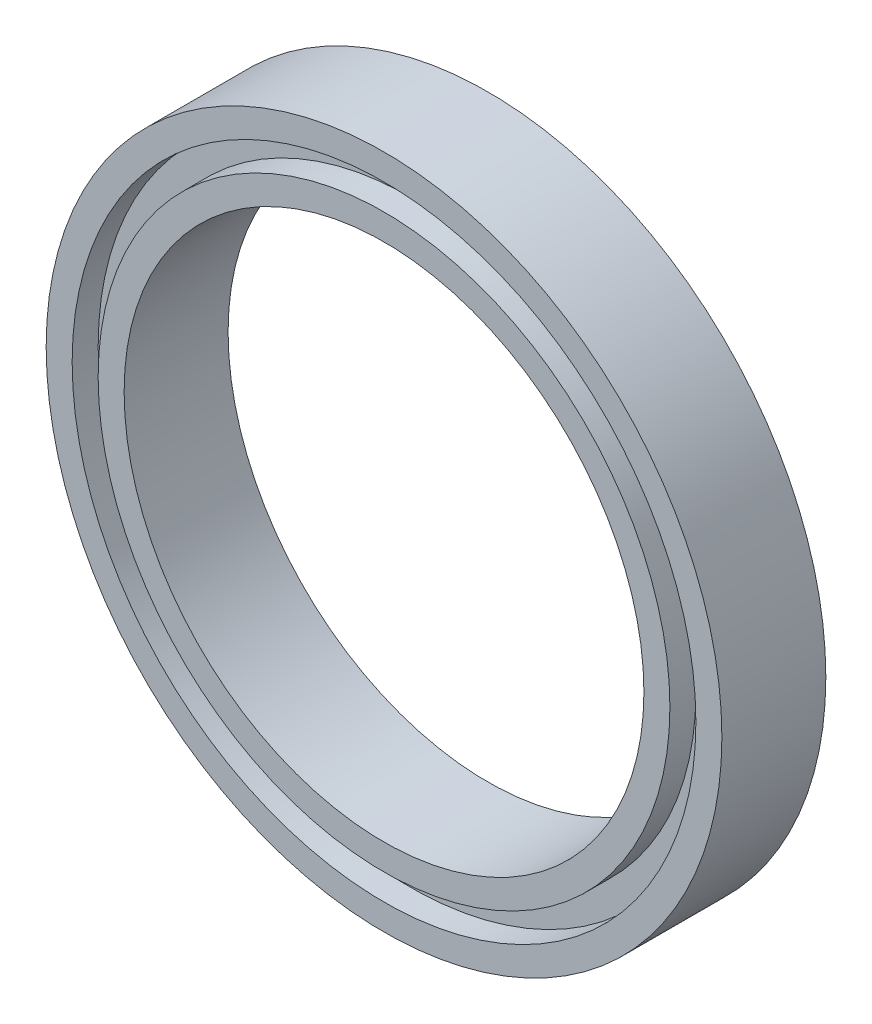
SolidWorks part; units mm, degrees
ref_plane "Front Plane" through (0, 0, 0) normal (0, 0, 1) x (1, 0, 0)
ref_plane "Top Plane" through (0, 0, 0) normal (0, 1, 0) x (1, 0, 0)
ref_plane "Right Plane" through (0, 0, 0) normal (1, 0, 0) x (0, 0, -1)
sketch "Sketch1" plane through (0, 0, 0) normal (0, 0, 1) x (1, 0, 0)
  circle A0 centre (0, 0) radius 25
  circle A1 centre (0, 0) radius 32.5
  dimension "D1" = 50
  dimension "D2" = 65
extrude "Boss-Extrude1" add sketch "Sketch1" along normal blind 10
sketch "Sketch2" plane through (0, 0, 10) normal (0, 0, 1) x (1, 0, 0)
  circle A0 centre (0, 0) radius 27.5
  circle A1 centre (0, 0) radius 30
  dimension "D1" = 55
  dimension "D2" = 2.5
extrude "Cut-Extrude1" cut sketch "Sketch2" against normal blind 2.5
